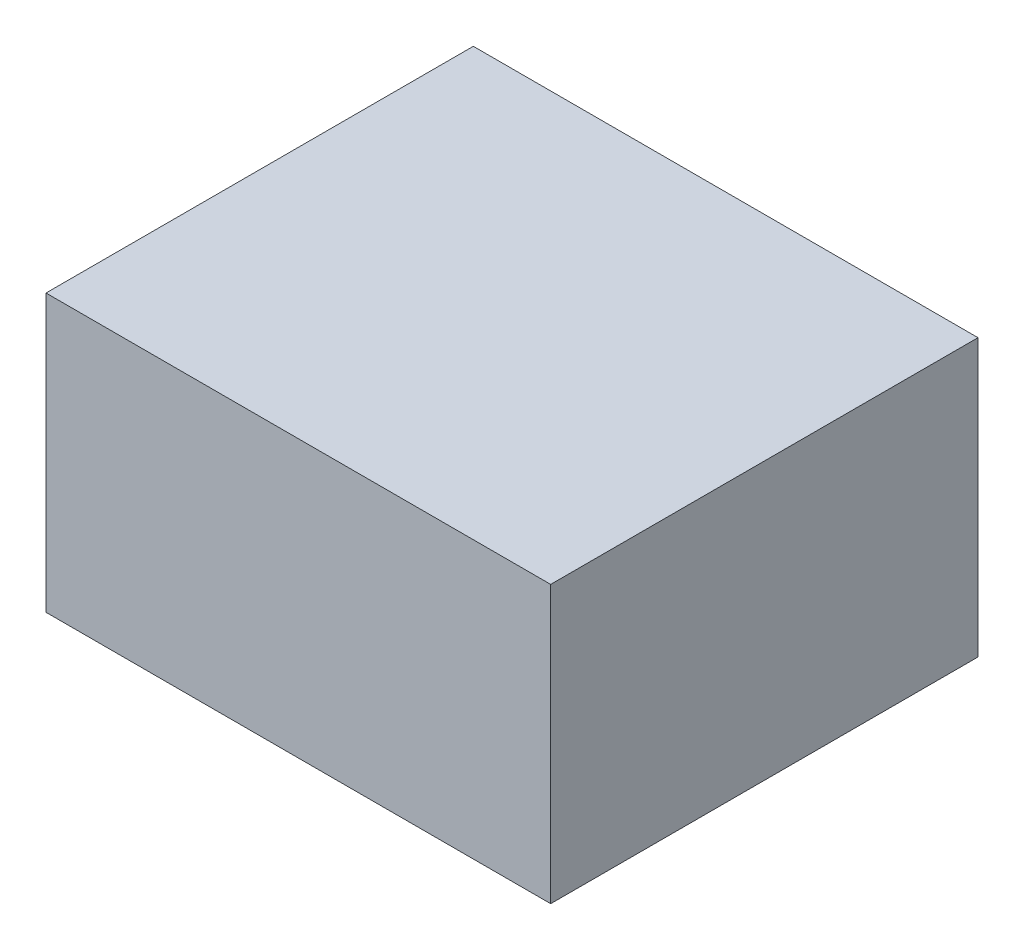
SolidWorks part; units mm, degrees
ref_plane "Front Plane" through (0, 0, 0) normal (0, 0, 1) x (1, 0, 0)
ref_plane "Top Plane" through (0, 0, 0) normal (0, 1, 0) x (1, 0, 0)
ref_plane "Right Plane" through (0, 0, 0) normal (1, 0, 0) x (0, 0, -1)
sketch "CurveSketch" plane through (0, 0, 0) normal (0, 0, 1) x (1, 0, 0)
  line L0 (-20.0525, -1.8635) -> (11.6665, -1.8635)
  line L1 (11.6665, -1.8635) -> (11.6665, 15.5175)
  line L2 (11.6665, 15.5175) -> (-20.0525, 15.5175)
  line L3 (-20.0525, 15.5175) -> (-20.0525, -1.8635)
extrude "CurveBoss" add sketch "CurveSketch" against normal blind 19.729 and the other way blind 7.127
